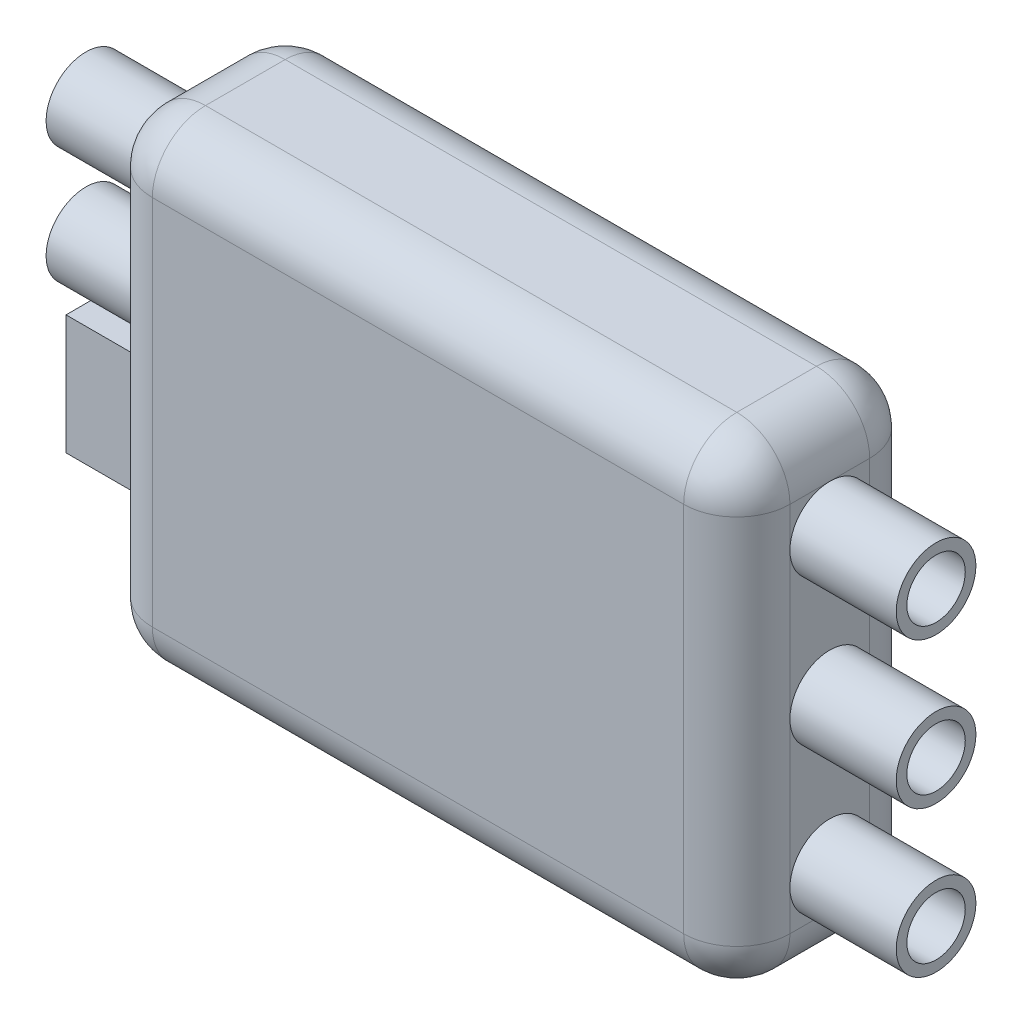
SolidWorks part; units mm, degrees
ref_plane "Front Plane" through (0, 0, 0) normal (0, 0, 1) x (1, 0, 0)
ref_plane "Top Plane" through (0, 0, 0) normal (0, 1, 0) x (1, 0, 0)
ref_plane "Right Plane" through (0, 0, 0) normal (1, 0, 0) x (0, 0, -1)
sketch "Sketch1" plane through (0, 0, 0) normal (0, 0, 1) x (1, 0, 0)
  line L1 (-10, -9) -> (10, -9)
  line L2 (-12, -7) -> (-12, 7)
  line L3 (-10, 9) -> (10, 9)
  line L4 (12, -7) -> (12, 7)
  line L5 (-12, -9) -> (12, 9) construction
  line L6 (-12, 9) -> (12, -9) construction
  arc A0 (-10, -9) -> (-12, -7) centre (-10, -7) cw
  arc A1 (10, -9) -> (12, -7) centre (10, -7) ccw
  arc A2 (10, 9) -> (12, 7) centre (10, 7) cw
  arc A3 (-12, 7) -> (-10, 9) centre (-10, 7) cw
  point P0 (0, 0)
  dimension "D3" = 2
  dimension "D1" = 24
  dimension "D2" = 18
extrude "Boss-Extrude1" add sketch "Sketch1" along normal blind 7
fillet "Fillet1" radius 2 16 edges at (0, -9, 0) (11.4142, -8.4142, 0) (12, 0, 0) (11.4142, 8.4142, 0) (0, 9, 0) (-11.4142, 8.4142, 0) (-12, 0, 0) (-11.4142, -8.4142, 0) (-12, 0, 7) (-11.4142, 8.4142, 7) (0, 9, 7) (11.4142, 8.4142, 7) (12, 0, 7) (11.4142, -8.4142, 7) (0, -9, 7) (-11.4142, -8.4142, 7)
sketch "Sketch3" plane through (12, 0, 0) normal (1, 0, 0) x (0, 0, -1)
  line L0 (0, 0) -> (-5, 0) construction
  line L1 (-5, 7) -> (-5, -7) construction
  line L2 (-3.5, 7) -> (-3.5, -7) construction
  line L3 (-5, 7) -> (-2, 7) construction
  line L4 (-5, -7) -> (-2, -7) construction
  circle A0 centre (-3.5, 0) radius 1.1
  circle A1 centre (-3.5, 0) radius 1.5
  circle A2 centre (-3.5, 5.5) radius 1.5
  circle A3 centre (-3.5, 5.5) radius 1.1
  circle A4 centre (-3.5, -5.5) radius 1.5
  circle A5 centre (-3.5, -5.5) radius 1.1
  dimension "D1" = 3
  dimension "D2" = 0.4
extrude "Boss-Extrude2" add sketch "Sketch3" along normal blind 4
sketch "Sketch4" plane through (-12, 0, 0) normal (-1, 0, 0) x (0, 0, 1)
  line L0 (3.5, 7) -> (3.5, -7) construction
  line L1 (5, 7) -> (2, 7) construction
  line L2 (5, -7) -> (2, -7) construction
  line L4 (2.75, -5.6979) -> (4.25, -5.6979)
  line L5 (2.75, -5.6979) -> (2.75, -1.1979)
  line L6 (2.75, -1.1979) -> (4.25, -1.1979)
  line L7 (4.25, -5.6979) -> (4.25, -1.1979)
  line L8 (2.75, -5.6979) -> (4.25, -1.1979) construction
  line L9 (2.75, -1.1979) -> (4.25, -5.6979) construction
  circle A0 centre (3.5, 5.5) radius 1.5
  circle A1 centre (3.5, 5.5) radius 1.1
  circle A2 centre (3.5, 1.1) radius 1.5
  circle A3 centre (3.5, 1.1) radius 1.1
  point P12 (3.5, -3.4479)
  point P17 (3.5, 1.7853)
  point P19 (3.4287, 6.527)
  point P20 (3.5502, 7.3438)
  dimension "D3" = 3
  dimension "D4" = 2.2
  dimension "D1" = 4.5
  dimension "D2" = 1.5
  dimension "D5" = 4.4
extrude "Boss-Extrude3" add sketch "Sketch4" along normal blind 4
